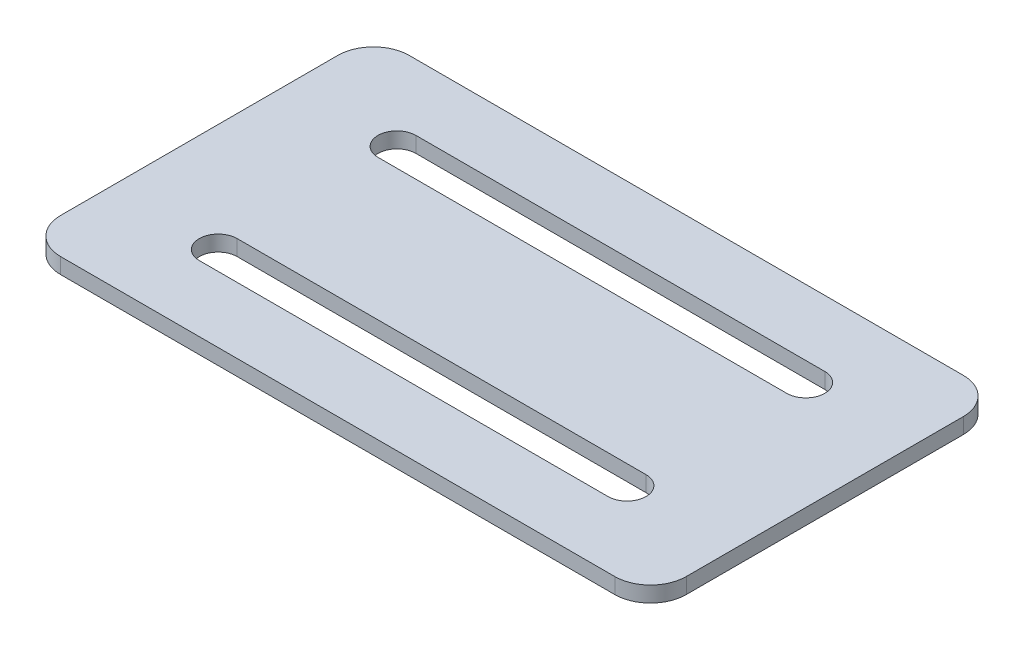
SolidWorks part; units mm, degrees
ref_plane "Front Plane" through (0, 0, 0) normal (0, 0, 1) x (1, 0, 0)
ref_plane "Top Plane" through (0, 0, 0) normal (0, 1, 0) x (1, 0, 0)
ref_plane "Right Plane" through (0, 0, 0) normal (1, 0, 0) x (0, 0, -1)
ref_plane "Plane1" through (468.8298, 0, 0) normal (1, 0, 0) x (0, 0, -1)
sketch "Sketch1" plane through (468.8298, 0, 0) normal (1, 0, 0) x (0, 0, -1)
  line L3 (-290.6247, 0) -> (-368.6247, 0)
  line L4 (-290.6247, 0) -> (-290.6247, 3.4987)
  line L5 (-290.6247, 3.4987) -> (-368.6247, 3.4987)
  line L6 (-368.6247, 0) -> (-368.6247, 3.4987)
extrude "Boss-Extrude1" add sketch "Sketch1" against normal up to surface (140 mm away)
fillet "Fillet1" radius 8 4 edges at (328.8298, 1.7493, 290.6247) (328.8298, 1.7493, 368.6247) (468.8298, 1.7493, 368.6247) (468.8298, 1.7493, 290.6247)
sketch "Sketch3" plane through (0, 3.4987, 0) normal (0, 1, 0) x (1, 0, 0)
  line L0 (353.0798, -345.3747) -> (444.5798, -345.3747) construction
  line L1 (353.0798, -353.8747) -> (444.5798, -353.8747) construction
  line L2 (353.0798, -305.3747) -> (444.5798, -305.3747) construction
  line L3 (353.0798, -313.8747) -> (444.5798, -313.8747) construction
  line L4 (353.0798, -345.3747) -> (444.5798, -345.3747)
  line L5 (353.0798, -353.8747) -> (444.5798, -353.8747)
  line L6 (353.0798, -305.3747) -> (444.5798, -305.3747)
  line L7 (353.0798, -313.8747) -> (444.5798, -313.8747)
  arc A0 (444.5798, -353.8747) -> (444.5798, -345.3747) centre (444.5798, -349.6247) ccw construction
  arc A1 (353.0798, -345.3747) -> (353.0798, -353.8747) centre (353.0798, -349.6247) ccw construction
  arc A2 (444.5798, -313.8747) -> (444.5798, -305.3747) centre (444.5798, -309.6247) ccw construction
  arc A3 (353.0798, -305.3747) -> (353.0798, -313.8747) centre (353.0798, -309.6247) ccw construction
  arc A4 (444.5798, -353.8747) -> (444.5798, -345.3747) centre (444.5798, -349.6247) ccw
  arc A5 (353.0798, -345.3747) -> (353.0798, -353.8747) centre (353.0798, -349.6247) ccw
  arc A6 (444.5798, -313.8747) -> (444.5798, -305.3747) centre (444.5798, -309.6247) ccw
  arc A7 (353.0798, -305.3747) -> (353.0798, -313.8747) centre (353.0798, -309.6247) ccw
extrude "Cut-Extrude1" cut sketch "Sketch3" against normal blind 10
